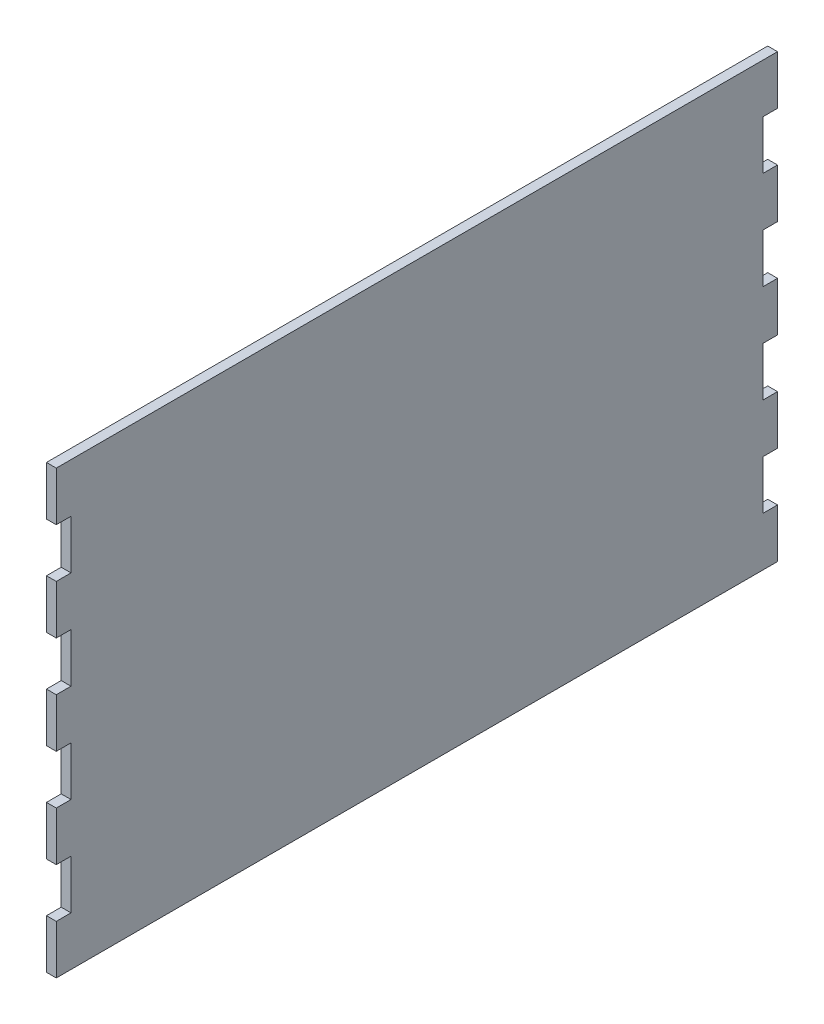
SolidWorks part; units mm, degrees
ref_plane "Front Plane" through (0, 0, 0) normal (0, 0, 1) x (1, 0, 0)
ref_plane "Top Plane" through (0, 0, 0) normal (0, 1, 0) x (1, 0, 0)
ref_plane "Right Plane" through (0, 0, 0) normal (1, 0, 0) x (0, 0, -1)
sketch "Sketch1" plane through (0, 0, 0) normal (1, 0, 0) x (0, 0, -1)
  line L0 (-294, 71.8494) -> (-294, 51.8494)
  line L1 (-300, 91.8494) -> (-6, 91.8494)
  line L2 (-300, 91.8494) -> (-300, 71.8494)
  line L3 (-300, -88.1506) -> (-6, -88.1506)
  line L5 (-153, 91.8494) -> (-153, -88.1506) construction
  line L6 (-300, 71.8494) -> (-294, 71.8494)
  line L7 (-300, 51.8494) -> (-294, 51.8494)
  line L8 (-300, 31.8494) -> (-294, 31.8494)
  line L9 (-300, 11.8494) -> (-294, 11.8494)
  line L10 (-300, -8.1506) -> (-294, -8.1506)
  line L11 (-300, -28.1506) -> (-294, -28.1506)
  line L12 (-300, -48.1506) -> (-294, -48.1506)
  line L13 (-300, -68.1506) -> (-294, -68.1506)
  line L14 (-300, 51.8494) -> (-300, 31.8494)
  line L15 (-300, 11.8494) -> (-300, -8.1506)
  line L16 (-300, -28.1506) -> (-300, -48.1506)
  line L17 (-300, -68.1506) -> (-300, -88.1506)
  line L18 (-294, 31.8494) -> (-294, 11.8494)
  line L19 (-294, -48.1506) -> (-294, -68.1506)
  line L20 (-294, -8.1506) -> (-294, -28.1506)
  line L21 (-12, -8.1506) -> (-12, -28.1506)
  line L22 (-12, -48.1506) -> (-12, -68.1506)
  line L23 (-12, 31.8494) -> (-12, 11.8494)
  line L24 (-6, -68.1506) -> (-6, -88.1506)
  line L25 (-6, -28.1506) -> (-6, -48.1506)
  line L26 (-6, 11.8494) -> (-6, -8.1506)
  line L27 (-6, 51.8494) -> (-6, 31.8494)
  line L28 (-6, -68.1506) -> (-12, -68.1506)
  line L29 (-6, -48.1506) -> (-12, -48.1506)
  line L30 (-6, -28.1506) -> (-12, -28.1506)
  line L31 (-6, -8.1506) -> (-12, -8.1506)
  line L32 (-6, 11.8494) -> (-12, 11.8494)
  line L33 (-6, 31.8494) -> (-12, 31.8494)
  line L34 (-6, 51.8494) -> (-12, 51.8494)
  line L35 (-6, 71.8494) -> (-12, 71.8494)
  line L36 (-6, 91.8494) -> (-6, 71.8494)
  line L37 (-12, 71.8494) -> (-12, 51.8494)
  point P0 (0, 0)
  dimension "D1" = 147
  dimension "D2" = 6
  dimension "D3" = 180
  dimension "D4" = 20
extrude "Boss-Extrude1" add sketch "Sketch1" along normal blind 4
